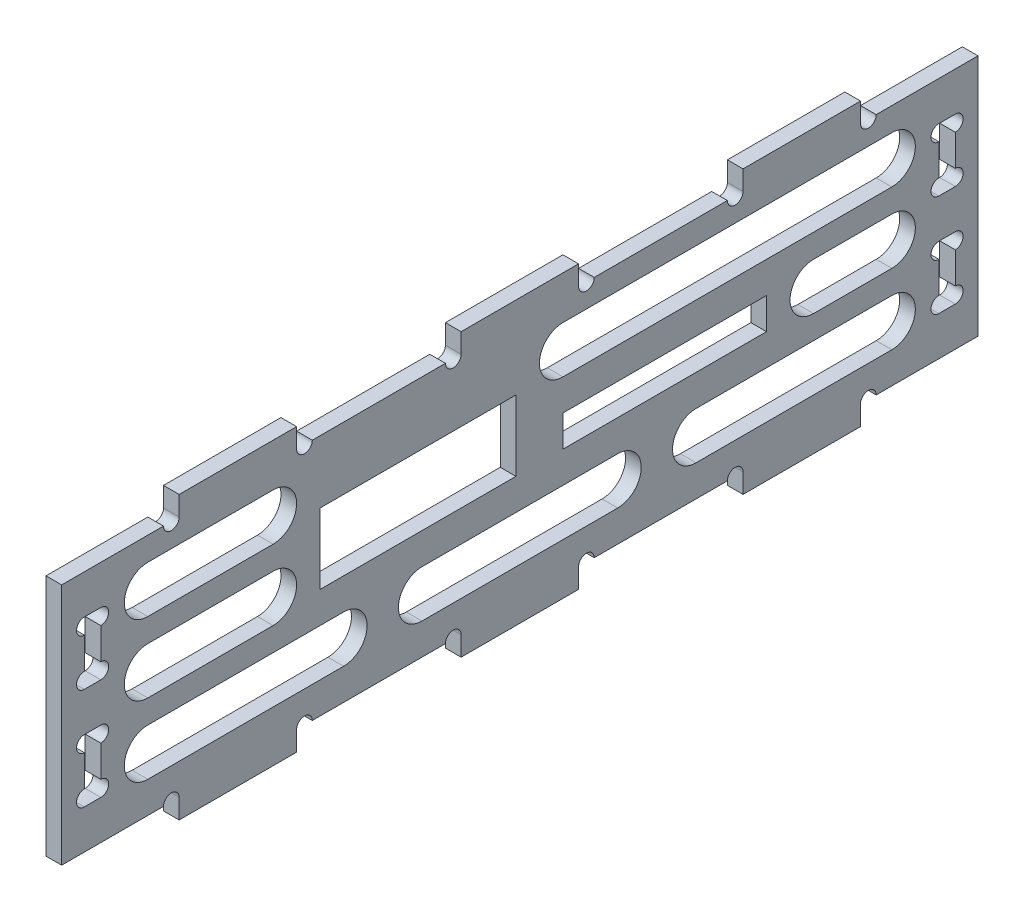
SolidWorks part; units mm, degrees
ref_plane "前视基准面" through (0, 0, 0) normal (0, 0, 1) x (1, 0, 0)
ref_plane "上视基准面" through (0, 0, 0) normal (0, 1, 0) x (1, 0, 0)
ref_plane "右视基准面" through (0, 0, 0) normal (1, 0, 0) x (0, 0, -1)
sketch "草图1" plane through (0, 0, 0) normal (1, 0, 0) x (0, 0, -1)
  line L1 (0, 0) -> (107, 0)
  line L2 (0, 0) -> (0, 31)
  line L3 (0, 31) -> (107, 31)
  line L4 (107, 0) -> (107, 31)
  line L5 (59, 18) -> (85, 18)
  line L6 (59, 18) -> (59, 14)
  line L7 (59, 14) -> (85, 14)
  line L8 (85, 18) -> (85, 14)
  line L9 (28, 23) -> (53, 23)
  line L10 (28, 23) -> (28, 14)
  line L11 (28, 14) -> (53, 14)
  line L12 (53, 23) -> (53, 14)
  dimension "D1" = 31
  dimension "D2" = 107
  dimension "D3" = 48
  dimension "D4" = 14
  dimension "D5" = 4
  dimension "D6" = 26
  dimension "D7" = 53
  dimension "D8" = 25
  dimension "D9" = 9
extrude "凸台-拉伸1" add sketch "草图1" along normal blind 2
sketch "草图2" plane through (2, 0, 0) normal (1, 0, 0) x (0, 0, -1)
  line L0 (0, 31) -> (-5, 31)
  line L1 (-5, 31) -> (-5, 0)
  line L2 (-5, 0) -> (0, 0)
  line L4 (0, 31) -> (0, 26)
  line L5 (0, 31) -> (0, 0) construction
  line L6 (0, 26) -> (-2.1, 26)
  line L7 (-2.1, 26) -> (-2.1, 18)
  line L8 (-2.1, 18) -> (0, 18)
  line L9 (0, 18) -> (0, 13)
  line L10 (0, 13) -> (-2.1, 13)
  line L11 (-2.1, 13) -> (-2.1, 5)
  line L12 (-2.1, 5) -> (0, 5)
  line L13 (0, 0) -> (0, 5)
  line L14 (53.5, 31) -> (53.5, 0) construction
  line L15 (107, 31) -> (0, 31) construction
  line L16 (0, 0) -> (107, 0) construction
  line L17 (107, 0) -> (107, 5)
  line L18 (109.1, 5) -> (107, 5)
  line L19 (109.1, 13) -> (109.1, 5)
  line L20 (107, 13) -> (109.1, 13)
  line L21 (107, 18) -> (107, 13)
  line L22 (109.1, 18) -> (107, 18)
  line L23 (109.1, 26) -> (109.1, 18)
  line L24 (107, 26) -> (109.1, 26)
  line L25 (107, 31) -> (107, 26)
  line L26 (112, 0) -> (107, 0)
  line L27 (112, 31) -> (112, 0)
  line L28 (107, 31) -> (112, 31)
  dimension "D1" = 5
  dimension "D2" = 8
  dimension "D3" = 5
  dimension "D4" = 8
  dimension "D5" = 2.1
  dimension "D6" = 5
extrude "凸台-拉伸2" add sketch "草图2" against normal up to surface (2 mm away) up to face at (0, 15.5, -53.5)
sketch "草图3" plane through (2, 0, 0) normal (1, 0, 0) x (0, 0, -1)
  line L0 (-2.1, 24) -> (-2.1, 26)
  line L1 (-2.1, 18) -> (-2.1, 26) construction
  line L2 (-1.05, 26) -> (-1.05, 18) construction
  line L3 (-2.1, 26) -> (0, 26) construction
  line L4 (0, 18) -> (-2.1, 18) construction
  line L5 (-2.1, 22) -> (0, 22) construction
  line L6 (0, 26) -> (0, 18) construction
  line L7 (0, 24) -> (0, 26)
  line L8 (0, 20) -> (0, 18)
  line L9 (-2.1, 20) -> (-2.1, 18)
  line L10 (-1.05, 18) -> (-1.05, 13) construction
  line L11 (-2.1, 13) -> (0, 13) construction
  line L12 (-1.05, 15.5) -> (0, 15.5) construction
  line L13 (-2.1, 9) -> (0, 9) construction
  line L14 (-1.05, 5) -> (-1.05, 13) construction
  line L15 (-2.1, 11) -> (-2.1, 13)
  line L16 (0, 11) -> (0, 13)
  line L17 (0, 7) -> (0, 5)
  line L18 (-2.1, 7) -> (-2.1, 5)
  line L19 (53.5, 31) -> (53.5, 0) construction
  line L20 (112, 31) -> (-5, 31) construction
  line L21 (-5, 0) -> (112, 0) construction
  line L22 (108.05, 5) -> (108.05, 13) construction
  line L23 (109.1, 9) -> (107, 9) construction
  line L24 (108.05, 15.5) -> (107, 15.5) construction
  line L25 (108.05, 18) -> (108.05, 13) construction
  line L26 (109.1, 22) -> (107, 22) construction
  line L27 (108.05, 26) -> (108.05, 18) construction
  line L28 (109.1, 7) -> (109.1, 5)
  line L29 (107, 7) -> (107, 5)
  line L30 (107, 11) -> (107, 13)
  line L31 (109.1, 11) -> (109.1, 13)
  line L32 (109.1, 20) -> (109.1, 18)
  line L33 (107, 20) -> (107, 18)
  line L34 (107, 24) -> (107, 26)
  line L35 (109.1, 24) -> (109.1, 26)
  line L36 (109.1, 26) -> (109.1, 18) construction
  arc A0 (-2.1, 26) -> (-2.1, 24) centre (-2.1, 25) ccw
  arc A1 (0, 26) -> (0, 24) centre (0, 25) cw
  arc A2 (0, 18) -> (0, 20) centre (0, 19) ccw
  arc A3 (-2.1, 18) -> (-2.1, 20) centre (-2.1, 19) cw
  arc A4 (-2.1, 13) -> (-2.1, 11) centre (-2.1, 12) ccw
  arc A5 (0, 13) -> (0, 11) centre (0, 12) cw
  arc A6 (0, 5) -> (0, 7) centre (0, 6) ccw
  arc A7 (-2.1, 5) -> (-2.1, 7) centre (-2.1, 6) cw
  arc A8 (109.1, 5) -> (109.1, 7) centre (109.1, 6) ccw
  arc A9 (107, 5) -> (107, 7) centre (107, 6) cw
  arc A10 (107, 13) -> (107, 11) centre (107, 12) ccw
  arc A11 (109.1, 13) -> (109.1, 11) centre (109.1, 12) cw
  arc A12 (109.1, 18) -> (109.1, 20) centre (109.1, 19) ccw
  arc A13 (107, 18) -> (107, 20) centre (107, 19) cw
  arc A14 (107, 26) -> (107, 24) centre (107, 25) ccw
  arc A15 (109.1, 26) -> (109.1, 24) centre (109.1, 25) cw
  dimension "D1" = 1
extrude "切除-拉伸1" cut sketch "草图3" against normal through all
sketch "草图5" plane through (2, 0, 0) normal (1, 0, 0) x (0, 0, -1)
  line L0 (112, 31) -> (-5, 31) construction
  line L1 (10, 31) -> (25, 31)
  line L2 (10, 31) -> (10, 33.5)
  line L3 (10, 33.5) -> (25, 33.5)
  line L4 (25, 31) -> (25, 33.5)
  line L5 (0, 24) -> (0, 20) construction
  line L6 (46, 31) -> (61, 31)
  line L7 (46, 31) -> (46, 33.5)
  line L8 (46, 33.5) -> (61, 33.5)
  line L9 (61, 31) -> (61, 33.5)
  line L10 (82, 31) -> (97, 31)
  line L11 (82, 31) -> (82, 33.5)
  line L12 (82, 33.5) -> (97, 33.5)
  line L13 (97, 31) -> (97, 33.5)
  line L14 (107, 20) -> (107, 24) construction
  line L15 (-5, 15.5) -> (112, 15.5) construction
  line L16 (-5, 31) -> (-5, 0) construction
  line L17 (112, 0) -> (112, 31) construction
  line L18 (97, 0) -> (97, -2.5)
  line L19 (82, -2.5) -> (97, -2.5)
  line L20 (82, 0) -> (82, -2.5)
  line L21 (82, 0) -> (97, 0)
  line L22 (61, 0) -> (61, -2.5)
  line L23 (46, -2.5) -> (61, -2.5)
  line L24 (46, 0) -> (46, -2.5)
  line L25 (46, 0) -> (61, 0)
  line L26 (25, 0) -> (25, -2.5)
  line L27 (10, -2.5) -> (25, -2.5)
  line L28 (10, 0) -> (10, -2.5)
  line L29 (10, 0) -> (25, 0)
  dimension "D1" = 10
  dimension "D2" = 15
  dimension "D3" = 15
  dimension "D4" = 21
  dimension "D5" = 10
  dimension "D6" = 15
  dimension "D7" = 2.5
extrude "凸台-拉伸3" add sketch "草图5" against normal up to surface (2 mm away) up to face at (0, 9, 1.05)
sketch "草图6" plane through (2, 0, 0) normal (1, 0, 0) x (0, 0, -1)
  line L0 (10, 31) -> (8, 31)
  line L1 (10, 31) -> (-5, 31) construction
  line L2 (17.5, 33.5) -> (17.5, -2.5) construction
  line L3 (25, 33.5) -> (10, 33.5) construction
  line L4 (10, -2.5) -> (25, -2.5) construction
  line L5 (-5, 15.5) -> (112, 15.5) construction
  line L7 (-5, 31) -> (-5, 0) construction
  line L8 (112, 0) -> (112, 31) construction
  line L9 (25, 31) -> (27, 31)
  line L10 (35.5, 31) -> (35.5, 0) construction
  line L11 (46, 31) -> (25, 31) construction
  line L12 (25, 0) -> (46, 0) construction
  line L13 (53.5, 33.5) -> (53.5, -2.5) construction
  line L14 (61, 33.5) -> (46, 33.5) construction
  line L15 (46, -2.5) -> (61, -2.5) construction
  line L16 (46, 31) -> (44, 31)
  line L18 (61, 31) -> (63, 31)
  line L19 (82, 31) -> (80, 31)
  line L20 (97, 31) -> (99, 31)
  line L21 (97, 0) -> (99, 0)
  line L22 (82, 0) -> (80, 0)
  line L23 (61, 0) -> (63, 0)
  line L24 (46, 0) -> (44, 0)
  line L25 (25, 0) -> (27, 0)
  line L26 (10, 0) -> (8, 0)
  arc A0 (10, 31) -> (8, 31) centre (9, 31) cw
  arc A1 (25, 31) -> (27, 31) centre (26, 31) ccw
  arc A2 (46, 31) -> (44, 31) centre (45, 31) cw
  arc A3 (61, 31) -> (63, 31) centre (62, 31) ccw
  arc A4 (82, 31) -> (80, 31) centre (81, 31) cw
  arc A5 (97, 31) -> (99, 31) centre (98, 31) ccw
  arc A6 (97, 0) -> (99, 0) centre (98, 0) cw
  arc A7 (82, 0) -> (80, 0) centre (81, 0) ccw
  arc A8 (61, 0) -> (63, 0) centre (62, 0) cw
  arc A9 (46, 0) -> (44, 0) centre (45, 0) ccw
  arc A10 (25, 0) -> (27, 0) centre (26, 0) cw
  arc A11 (10, 0) -> (8, 0) centre (9, 0) ccw
  dimension "D1" = 1
extrude "切除-拉伸2" cut sketch "草图6" against normal through all
sketch "草图7" plane through (2, 0, 0) normal (1, 0, 0) x (0, 0, -1)
  line L0 (6, 25) -> (22, 25) construction
  line L1 (6, 28) -> (22, 28)
  line L2 (6, 22) -> (22, 22)
  line L6 (6, 7) -> (31, 7) construction
  line L7 (6, 10) -> (31, 10)
  line L8 (6, 4) -> (31, 4)
  line L9 (28, 23) -> (28, 14) construction
  line L10 (0, 24) -> (0, 20) construction
  line L11 (53, 23) -> (28, 23) construction
  line L12 (6, 16) -> (22, 16) construction
  line L13 (6, 19) -> (22, 19)
  line L14 (6, 13) -> (22, 13)
  line L15 (41, 7) -> (66, 7) construction
  line L16 (41, 10) -> (66, 10)
  line L17 (41, 4) -> (66, 4)
  line L18 (76, 7) -> (101, 7) construction
  line L19 (76, 10) -> (101, 10)
  line L20 (76, 4) -> (101, 4)
  line L21 (107, 7) -> (107, 11) construction
  line L22 (59, 25) -> (101, 25) construction
  line L23 (59, 28) -> (101, 28)
  line L24 (59, 22) -> (101, 22)
  line L25 (91, 16) -> (101, 16) construction
  line L26 (91, 19) -> (101, 19)
  line L27 (91, 13) -> (101, 13)
  line L28 (53, 14) -> (53, 23) construction
  line L29 (85, 14) -> (85, 18) construction
  arc A0 (6, 28) -> (6, 22) centre (6, 25) ccw
  arc A1 (22, 22) -> (22, 28) centre (22, 25) ccw
  arc A4 (6, 10) -> (6, 4) centre (6, 7) ccw
  arc A5 (31, 4) -> (31, 10) centre (31, 7) ccw
  arc A6 (6, 19) -> (6, 13) centre (6, 16) ccw
  arc A7 (22, 13) -> (22, 19) centre (22, 16) ccw
  arc A8 (41, 10) -> (41, 4) centre (41, 7) ccw
  arc A9 (66, 4) -> (66, 10) centre (66, 7) ccw
  arc A10 (76, 10) -> (76, 4) centre (76, 7) ccw
  arc A11 (101, 4) -> (101, 10) centre (101, 7) ccw
  arc A12 (59, 28) -> (59, 22) centre (59, 25) ccw
  arc A13 (101, 22) -> (101, 28) centre (101, 25) ccw
  arc A14 (91, 19) -> (91, 13) centre (91, 16) ccw
  arc A15 (101, 13) -> (101, 19) centre (101, 16) ccw
  point P2 (14, 25)
  point P14 (18.5, 7)
  point P23 (14, 16)
  point P29 (53.5, 7)
  point P38 (88.5, 7)
  point P47 (80, 25)
  point P52 (96, 16)
  dimension "D2" = 3
  dimension "D1" = 6
  dimension "D3" = 6
  dimension "D4" = 2
  dimension "D6" = 9
  dimension "D7" = 9
  dimension "D8" = 25
  dimension "D10" = 6
  dimension "D11" = 6
  dimension "D12" = 6
  dimension "D5" = 2
  dimension "D9" = 3
extrude "切除-拉伸3" cut sketch "草图7" against normal through all
